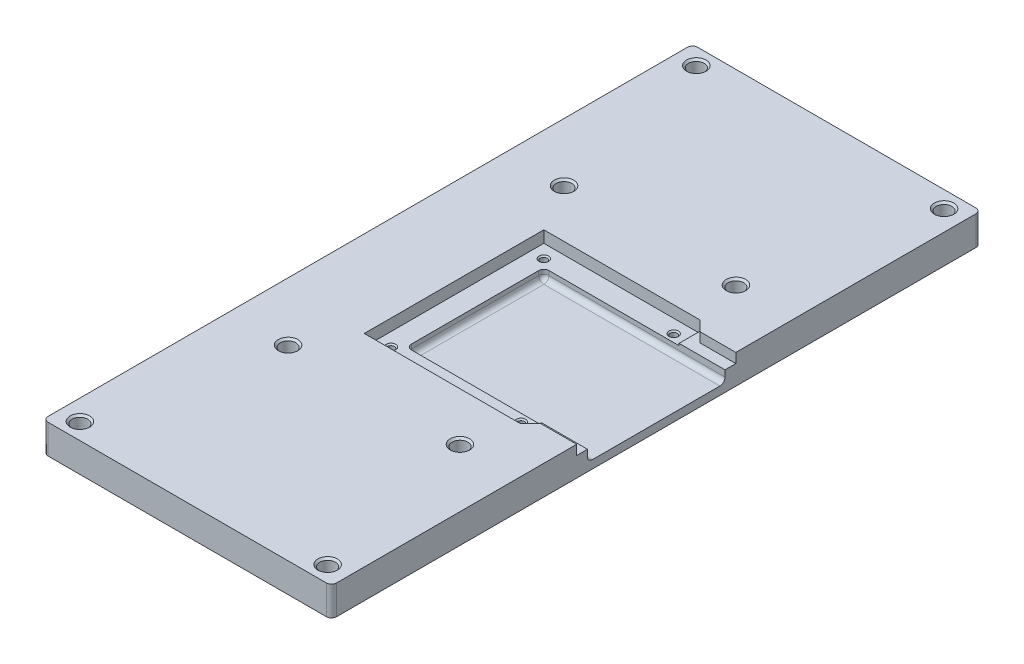
SolidWorks part; units mm, degrees
ref_plane "Front Plane" through (0, 0, 0) normal (0, 0, 1) x (1, 0, 0)
ref_plane "Top Plane" through (0, 0, 0) normal (0, 1, 0) x (1, 0, 0)
ref_plane "Right Plane" through (0, 0, 0) normal (1, 0, 0) x (0, 0, -1)
sketch "Sketch1" plane through (0, 0, 0) normal (0, 1, 0) x (1, 0, 0)
  line L0 (0, -112.5) -> (0, 112.5) construction
  line L1 (56.625, 112.5) -> (-56.625, 112.5) construction
  line L2 (-56.625, 112.5) -> (-56.625, -112.5)
  line L3 (-56.625, 0) -> (56.625, 0) construction
  line L4 (-56.625, 112.5) -> (-56.625, 125.5)
  line L5 (-54.625, 127.5) -> (54.625, 127.5)
  line L6 (0, 127.5) -> (0, 112.5) construction
  line L7 (56.625, 112.5) -> (56.625, 125.5)
  line L8 (56.625, 112.5) -> (56.625, -112.5)
  line L9 (0, -127.5) -> (0, -112.5) construction
  line L10 (56.625, -112.5) -> (-56.625, -112.5) construction
  line L11 (56.625, -112.5) -> (56.625, -125.5)
  line L12 (-54.625, -127.5) -> (54.625, -127.5)
  line L13 (-56.625, -112.5) -> (-56.625, -125.5)
  line L14 (-56.625, 115.5) -> (56.625, 115.5) construction
  circle A1 centre (-48.625, 121) radius 3.075 construction
  circle A2 centre (48.625, 121) radius 3.075 construction
  circle A5 centre (48.625, -121) radius 3.075 construction
  circle A6 centre (-48.625, -121) radius 3.075 construction
  arc A8 (-54.625, -127.5) -> (-56.625, -125.5) centre (-54.625, -125.5) cw
  arc A9 (56.625, -125.5) -> (54.625, -127.5) centre (54.625, -125.5) cw
  arc A10 (56.625, 125.5) -> (54.625, 127.5) centre (54.625, 125.5) ccw
  arc A11 (-56.625, 125.5) -> (-54.625, 127.5) centre (-54.625, 125.5) cw
  circle A12 centre (-33.75, 54.175) radius 3.075 construction
  circle A13 centre (33.75, 54.175) radius 3.075 construction
  circle A14 centre (33.75, -54.175) radius 3.075 construction
  circle A15 centre (-33.75, -54.175) radius 3.075 construction
  point P6 (0, 0)
  point P17 (0, 0)
  point P24 (0, 0)
  point P36 (-56.625, -127.5)
  point P39 (56.625, -127.5)
  point P42 (56.625, 127.5)
  point P45 (-56.625, 127.5)
  dimension "D5" = 54.175
  dimension "D10" = 2
  dimension "D3" = 6.15
  dimension "D1" = 56.625
  dimension "D2" = 112.5
  dimension "D4" = 6.5
  dimension "D6" = 8
  dimension "D7" = 8.5
  dimension "D8" = 12
  dimension "D9" = 3
  dimension "D11" = 127.5
  dimension "D12" = 33.75
extrude "Boss-Extrude1" add sketch "Sketch1" along normal blind 11.5
sketch "Sketch3" plane through (0, 11.5, 0) normal (0, 1, 0) x (1, 0, 0)
  line L0 (0, 0) -> (-56.625, 0) construction
  line L1 (-56.625, 125.5) -> (-56.625, -125.5) construction
  line L2 (0, 0) -> (0, 127.5) construction
  line L3 (54.625, 127.5) -> (-54.625, 127.5) construction
  line L4 (3.96, -16.3) -> (3.96, 16.3)
  line L5 (-2.46, -17.8) -> (2.46, -17.8)
  line L6 (-3.96, 16.3) -> (-3.96, -16.3)
  line L7 (2.46, 17.8) -> (-2.46, 17.8)
  line L8 (0, 17.8) -> (0, -17.8) construction
  line L9 (13.25, 0) -> (0, 0) construction
  line L10 (16.15, 10.025) -> (10.35, 10.025)
  line L11 (16.15, 10.025) -> (16.15, -10.025)
  line L12 (16.15, -10.025) -> (10.35, -10.025)
  line L13 (10.35, 10.025) -> (10.35, -10.025)
  line L14 (16.15, 10.025) -> (10.35, -10.025) construction
  line L15 (16.15, -10.025) -> (10.35, 10.025) construction
  line L16 (13.25, 0) -> (13.25, 10.025) construction
  line L17 (-16.15, 10.025) -> (-16.15, -10.025)
  line L18 (-16.15, -10.025) -> (-10.35, -10.025)
  line L23 (-16.15, 10.025) -> (-10.35, 10.025)
  line L24 (-10.35, 10.025) -> (-10.35, -10.025)
  arc A0 (-2.46, 17.8) -> (-3.96, 16.3) centre (-2.46, 16.3) ccw
  arc A1 (3.96, 16.3) -> (2.46, 17.8) centre (2.46, 16.3) ccw
  arc A2 (2.46, -17.8) -> (3.96, -16.3) centre (2.46, -16.3) ccw
  arc A3 (-3.96, -16.3) -> (-2.46, -17.8) centre (-2.46, -16.3) ccw
  point P9 (0, 0)
  point P23 (0, 0)
  dimension "D2" = 1.5
  dimension "D1" = 35.6
  dimension "D3" = 7.92
  dimension "D4" = 20.05
  dimension "D5" = 5.8
  dimension "D6" = 13.25
sketch "Sketch4" plane through (0, 11.5, 0) normal (0, 1, 0) x (1, 0, 0)
  circle A0 centre (-48.625, -121) radius 3.075 construction
  circle A1 centre (48.625, -121) radius 3.075 construction
  circle A2 centre (48.625, 121) radius 3.075 construction
  circle A3 centre (-33.75, -54.175) radius 3.075 construction
  circle A4 centre (33.75, -54.175) radius 3.075 construction
  circle A5 centre (-48.625, 121) radius 3.075 construction
  circle A6 centre (33.75, 54.175) radius 3.075 construction
  circle A7 centre (-33.75, 54.175) radius 3.075 construction
  circle A8 centre (-48.625, -121) radius 3.075
  circle A9 centre (48.625, -121) radius 3.075
  circle A10 centre (48.625, 121) radius 3.075
  circle A13 centre (-48.625, 121) radius 3.075
  circle A14 centre (-33.75, -54.175) radius 3.075
  circle A15 centre (33.75, -54.175) radius 3.075
  circle A16 centre (33.75, 54.175) radius 3.075
  circle A17 centre (-33.75, 54.175) radius 3.075
extrude "Cut-Extrude1" cut sketch "Sketch4" against normal blind 6
sketch "Sketch21" plane through (0, 11.5, 0) normal (0, 1, 0) x (1, 0, 0)
  line L0 (38.5, 35) -> (-22.5, 35) construction
  line L1 (38.5, 35) -> (42.5, 31) construction
  line L2 (-22.5, 35) -> (-22.5, -35) construction
  line L3 (-22.5, 0) -> (0, 0) construction
  line L4 (0, 0) -> (38.5, 0) construction
  line L5 (38.5, -35) -> (38.5, 35) construction
  line L6 (38.5, -35) -> (-22.5, -35) construction
  line L7 (42.5, 31) -> (56.625, 31) construction
  line L8 (56.625, -125.5) -> (56.625, 125.5) construction
  line L9 (56.625, 31) -> (56.625, -31)
  line L10 (56.625, 0) -> (38.5, 0) construction
  line L11 (42.5, -31) -> (56.625, -31) construction
  line L12 (38.5, -35) -> (42.5, -31) construction
  line L13 (42.6036, 31.25) -> (56.625, 31.25)
  line L14 (38.6036, 35.25) -> (42.6036, 31.25)
  line L15 (38.6036, 35.25) -> (-22.75, 35.25)
  line L16 (-22.75, 35.25) -> (-22.75, -35.25)
  line L17 (38.6036, -35.25) -> (-22.75, -35.25)
  line L18 (38.6036, -35.25) -> (42.6036, -31.25)
  line L19 (42.6036, -31.25) -> (56.625, -31.25)
  line L20 (56.625, -31.25) -> (56.625, -31)
  line L21 (56.625, 31) -> (56.625, 31.25)
  circle A0 centre (-17.5, 30) radius 1.6 construction
  circle A1 centre (33.5, 30) radius 1.6 construction
  circle A2 centre (33.5, -30) radius 1.6 construction
  circle A3 centre (-17.5, -30) radius 1.6 construction
  dimension "D8" = 3.2
  dimension "D1" = 22.5
  dimension "D2" = 61
  dimension "D3" = 35
  dimension "D4" = 5
  dimension "D5" = 5
  dimension "D6" = 5
  dimension "D7" = 5
  dimension "D9" = 45
  dimension "D10" = 4
  dimension "D12" = 14.125
  dimension "D11" = 0.25
extrude "Cut-Extrude6" cut sketch "Sketch21" against normal blind 4.6
sketch "Sketch24" plane through (0, 6.9, 0) normal (0, 1, 0) x (1, 0, 0)
  line L0 (56.625, 27) -> (-14.5, 27)
  line L2 (-14.5, 27) -> (-14.5, -27)
  line L3 (-14.5, -27) -> (56.625, -27)
  line L4 (56.625, -27) -> (56.625, 27)
  line L8 (38.5, 35) -> (-22.5, 35) construction
  line L10 (-22.5, 35) -> (-22.5, -35) construction
  line L11 (38.5, -35) -> (-22.5, -35) construction
  line L12 (56.625, -31.25) -> (56.625, 31.25) construction
  dimension "D1" = 8
  dimension "D2" = 8
  dimension "D3" = 8
extrude "Cut-Extrude3" cut sketch "Sketch24" against normal blind 3.7 and the other way through all
sketch "Sketch25" plane through (0, 6.9, 0) normal (0, 1, 0) x (1, 0, 0)
  circle A0 centre (33.5, 30) radius 1.35
  circle A1 centre (-17.5, 30) radius 1.35
  circle A2 centre (33.5, -30) radius 1.35
  circle A3 centre (-17.5, -30) radius 1.35
  dimension "D1" = 2.7
extrude "Cut-Extrude4" cut sketch "Sketch25" against normal blind 5
chamfer "Chamfer4" distance 0.5 angle 45 4 edges at (-17.5, 6.9, 31.35) (33.5, 6.9, 31.35) (33.5, 6.9, -28.65) (-17.5, 6.9, -28.65)
fillet "Fillet1" radius 2 5 edges at (21.0625, 3.2, 27) (-14.5, 5.05, 27) (-14.5, 5.05, -27) (-14.5, 3.2, 0) (21.0625, 3.2, -27)
sketch "Sketch26" plane through (0, 6.9, 0) normal (0, 1, 0) x (1, 0, 0)
  line L0 (0, 0) -> (56.625, 0) construction
  line L1 (56.625, -25) -> (56.625, 25) construction
  line L2 (38.6036, 35.25) -> (38.6036, 27)
  line L3 (56.625, 27) -> (-12.5, 27) construction
  line L4 (38.6036, 27) -> (56.625, 27)
  line L5 (56.625, 27) -> (56.625, 31.25)
  line L6 (56.625, 31.25) -> (42.6036, 31.25)
  line L7 (42.6036, 31.25) -> (38.6036, 35.25)
  line L8 (42.6036, -31.25) -> (38.6036, -35.25)
  line L9 (56.625, -31.25) -> (42.6036, -31.25)
  line L10 (56.625, -27) -> (56.625, -31.25)
  line L11 (38.6036, -27) -> (56.625, -27)
  line L12 (38.6036, -35.25) -> (38.6036, -27)
extrude "Boss-Extrude2" add sketch "Sketch26" along normal blind 0.8
chamfer "Chamfer5" distance 0.75 angle 45 8 edges at (48.625, 11.5, 124.075) (-48.625, 11.5, 124.075) (-48.625, 11.5, -117.925) (48.625, 11.5, -117.925) (33.75, 11.5, -51.1) (-33.75, 11.5, -51.1) (-33.75, 11.5, 57.25) (33.75, 11.5, 57.25)
equation "\"D5@Sketch21\"=\"D4@Sketch21\""
equation "\"D6@Sketch21\"=\"D4@Sketch21\""
equation "\"D7@Sketch21\"=\"D4@Sketch21\""
equation "\"D2@Sketch24\"=\"D1@Sketch24\""
equation "\"D3@Sketch24\"=\"D1@Sketch24\""
